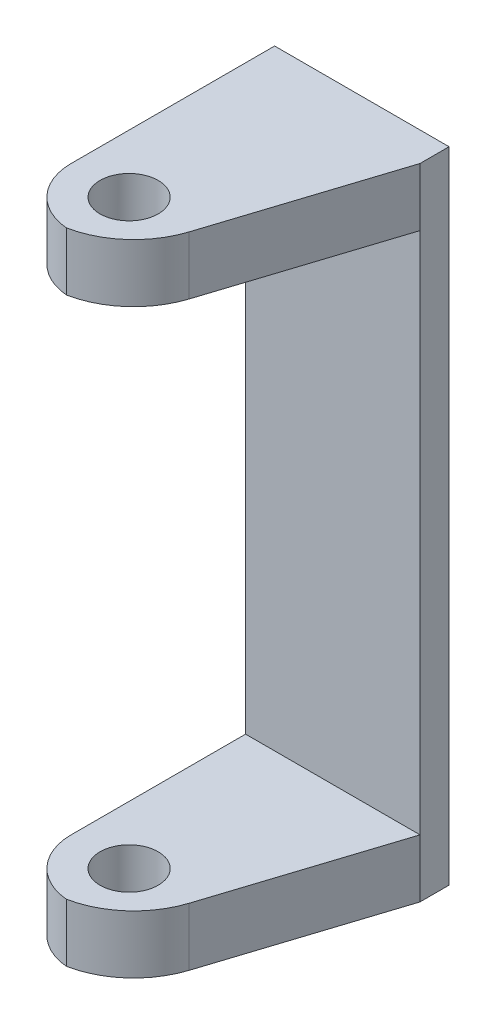
SolidWorks part; units mm, degrees
ref_plane "Front Plane" through (0, 0, 0) normal (0, 0, 1) x (1, 0, 0)
ref_plane "Top Plane" through (0, 0, 0) normal (0, 1, 0) x (1, 0, 0)
ref_plane "Right Plane" through (0, 0, 0) normal (1, 0, 0) x (0, 0, -1)
sketch "Sketch1" plane through (0, 0, 0) normal (0, 0, 1) x (1, 0, 0)
  line L0 (0, 0) -> (0, 110)
  line L1 (0, 110) -> (30, 110)
  line L2 (30, 110) -> (30, 0)
  line L3 (30, 0) -> (0, 0)
  dimension "D1" = 110
  dimension "D2" = 30
extrude "Boss-Extrude1" add sketch "Sketch1" along normal blind 5
sketch "Sketch3" plane through (0, 110, 0) normal (0, 1, 0) x (1, 0, 0)
  line L0 (0, -5) -> (0, -35.0318)
  line L1 (20.3387, -35.0318) -> (30, -5)
  line L2 (30, 0) -> (0, 0) construction
  line L3 (0, -5) -> (0, 0) construction
  line L4 (0, -5) -> (30, -5)
  arc A0 (0, -35.0318) -> (9.2027, -45) centre (10, -35.0318) ccw
  circle A2 centre (10, -35.0318) radius 5
  arc A3 (20.3387, -35.0318) -> (9.2027, -45) centre (6.2531, -30.5004) cw
  dimension "D1" = 45
  dimension "D2" = 10
  dimension "D3" = 10
  dimension "D5" = 9.2027
  dimension "D7" = 20.3387
extrude "Boss-Extrude3" add sketch "Sketch3" against normal through all
sketch "Sketch5" plane through (0, 0, 0) normal (1, 0, 0) x (0, 0, -1)
  line L0 (-45, 100) -> (-5, 100)
  line L1 (-45, 0) -> (-45, 110) construction
  line L2 (-5, 0) -> (-5, 110) construction
  line L3 (-5, 100) -> (-5, 10)
  line L4 (-5, 10) -> (-45, 10)
  line L5 (-45, 10) -> (-45, 100)
  line L6 (-35.0318, 0) -> (-5, 0) construction
  line L7 (-35.0318, 110) -> (-5, 110) construction
  dimension "D1" = 10
  dimension "D2" = 10
extrude "Cut-Extrude3" cut sketch "Sketch5" along normal through all both and the other way through all
